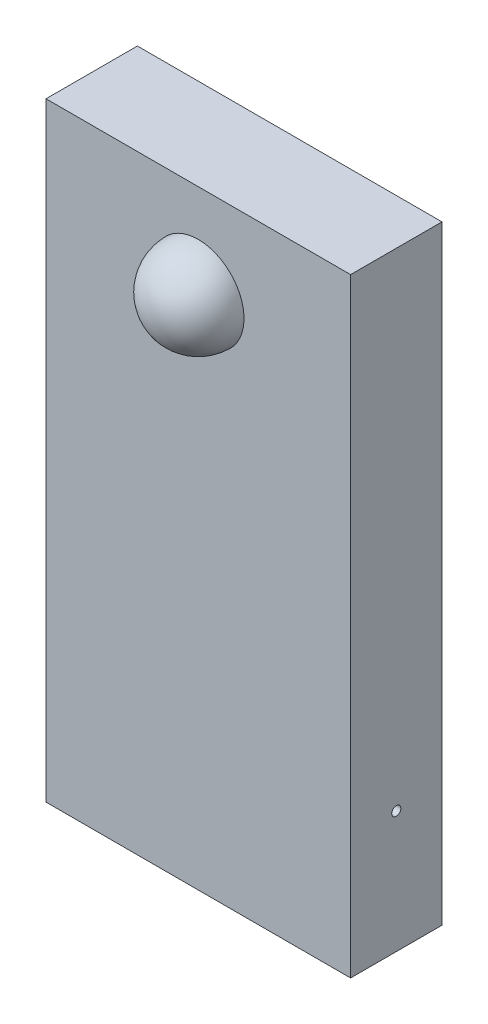
SolidWorks part; units mm, degrees
ref_plane "前基準面" through (0, 0, 0) normal (0, 0, 1) x (1, 0, 0)
ref_plane "上基準面" through (0, 0, 0) normal (0, 1, 0) x (1, 0, 0)
ref_plane "右基準面" through (0, 0, 0) normal (1, 0, 0) x (0, 0, -1)
sketch "草圖1" plane through (0, 0, 0) normal (0, 1, 0) x (1, 0, 0)
  line L1 (-50, -15) -> (50, -15)
  line L2 (-50, -15) -> (-50, 15)
  line L3 (-50, 15) -> (50, 15)
  line L4 (50, -15) -> (50, 15)
  line L5 (-50, -15) -> (50, 15) construction
  line L6 (-50, 15) -> (50, -15) construction
  point P0 (0, 0)
  dimension "D1" = 100
  dimension "D2" = 30
extrude "填料-伸長1" add sketch "草圖1" along normal blind 200
sketch "草圖2" plane through (0, 0, 15) normal (0, 0, 1) x (1, 0, 0)
  line L0 (-33.1568, 170) -> (61.8625, 170) construction
  line L1 (-50, 200) -> (50, 200) construction
  line L2 (-15, 170) -> (15, 170)
  arc A0 (15, 170) -> (-15, 170) centre (0, 170) ccw
  point P6 (0, 200)
  dimension "D1" = 30
  dimension "D2" = 30
revolve "旋轉5" add sketch "草圖2" angle 360 about L0
sketch "草圖3" plane through (-50, 0, 0) normal (-1, 0, 0) x (0, 0, 1)
  circle A0 centre (0, 40) radius 1.5
  dimension "D1" = 3
  dimension "D2" = 40
extrude "除料-伸長1" cut sketch "草圖3" against normal blind 200
